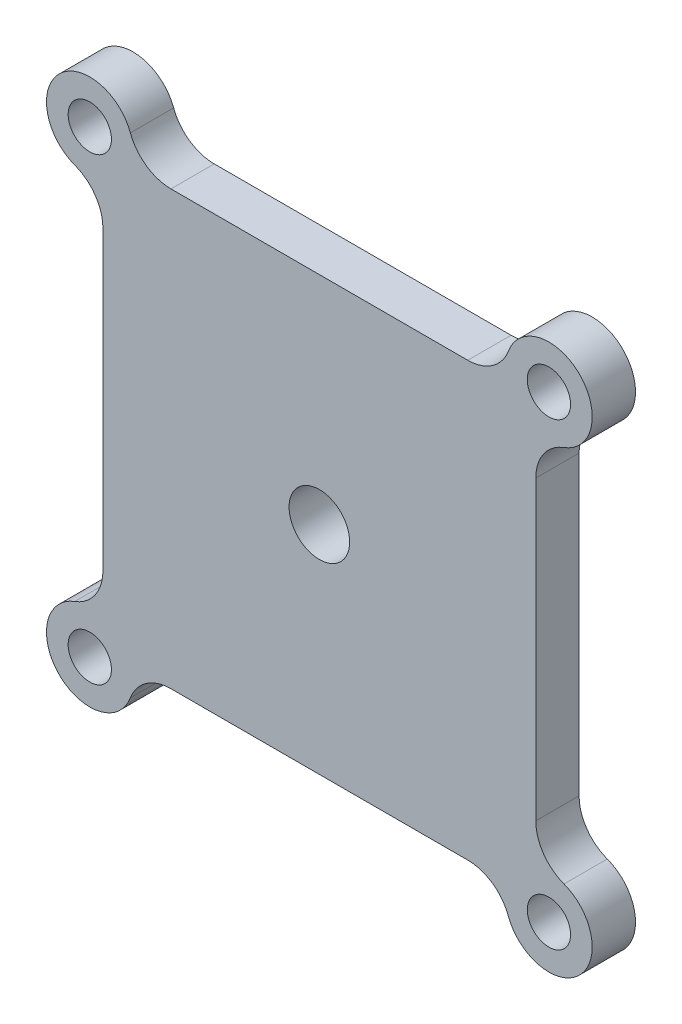
SolidWorks part; units mm, degrees
ref_plane "Front" through (0, 0, 0) normal (0, 0, 1) x (1, 0, 0)
ref_plane "Top" through (0, 0, 0) normal (0, 1, 0) x (1, 0, 0)
ref_plane "Right" through (0, 0, 0) normal (1, 0, 0) x (0, 0, -1)
sketch "Эскиз1" plane through (0, 0, 0) normal (0, 0, 1) x (1, 0, 0)
  line L1 (-17.1429, -25) -> (17.1429, -25)
  line L2 (-25, -17.1429) -> (-25, 17.1429)
  line L3 (-17.1429, 25) -> (17.1429, 25)
  line L4 (25, -17.1429) -> (25, 17.1429)
  line L5 (-25, -25) -> (25, 25) construction
  line L6 (-25, 25) -> (25, -25) construction
  circle A0 centre (0, 0) radius 3.5
  arc A4 (17.1429, 25) -> (21.8297, 28.2583) centre (17.1429, 30) ccw
  arc A6 (-21.8297, 28.2583) -> (-28.2583, 21.8297) centre (-26.5165, 26.5165) ccw
  circle A7 centre (-26.5165, 26.5165) radius 2.5
  arc A8 (-17.1429, 25) -> (-21.8297, 28.2583) centre (-17.1429, 30) cw
  arc A9 (-25, 17.1429) -> (-28.2583, 21.8297) centre (-30, 17.1429) ccw
  arc A10 (28.2583, 21.8297) -> (21.8297, 28.2583) centre (26.5165, 26.5165) ccw
  circle A11 centre (26.5165, 26.5165) radius 2.5
  arc A12 (25, 17.1429) -> (28.2583, 21.8297) centre (30, 17.1429) cw
  arc A13 (25, -17.1429) -> (28.2583, -21.8297) centre (30, -17.1429) ccw
  arc A14 (21.8297, -28.2583) -> (28.2583, -21.8297) centre (26.5165, -26.5165) ccw
  circle A15 centre (26.5165, -26.5165) radius 2.5
  arc A16 (17.1429, -25) -> (21.8297, -28.2583) centre (17.1429, -30) cw
  arc A17 (-17.1429, -25) -> (-21.8297, -28.2583) centre (-17.1429, -30) ccw
  arc A18 (-28.2583, -21.8297) -> (-21.8297, -28.2583) centre (-26.5165, -26.5165) ccw
  circle A19 centre (-26.5165, -26.5165) radius 2.5
  arc A20 (-25, -17.1429) -> (-28.2583, -21.8297) centre (-30, -17.1429) cw
  point P56 (0, 0)
  dimension "D5" = 7
  dimension "D8" = 10
  dimension "D9" = 5
  dimension "D10" = 5
  dimension "D11" = 5
  dimension "D1" = 50
  dimension "D2" = 50
  dimension "D3" = 25
  dimension "D4" = 25
  dimension "D12" = 4
extrude "Бобышка-Вытянуть1" add sketch "Эскиз1" along normal blind 5
